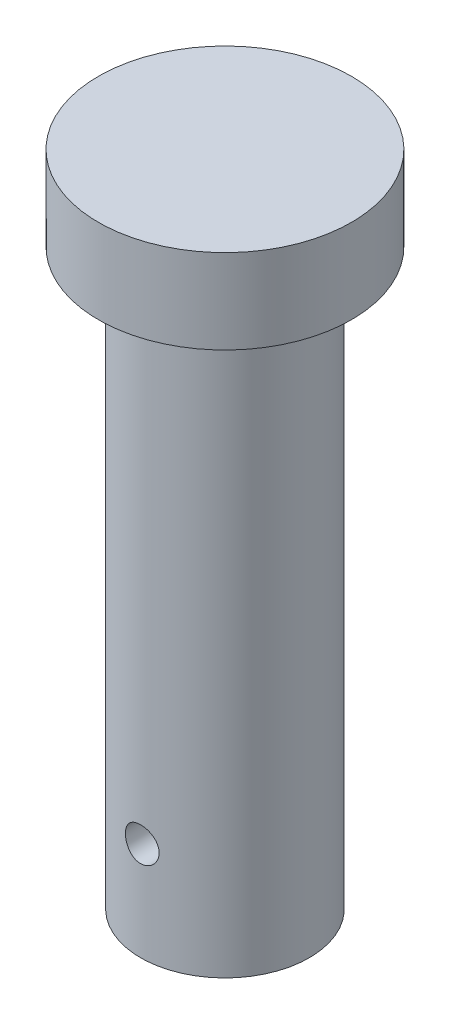
SolidWorks part; units mm, degrees
ref_plane "Front Plane" through (0, 0, 0) normal (0, 0, 1) x (1, 0, 0)
ref_plane "Top Plane" through (0, 0, 0) normal (0, 1, 0) x (1, 0, 0)
ref_plane "Right Plane" through (0, 0, 0) normal (1, 0, 0) x (0, 0, -1)
sketch "Sketch1" plane through (0, 0, 0) normal (0, 0, 1) x (1, 0, 0)
  line L0 (0, 0) -> (0, 117)
  line L1 (0, 117) -> (22.5, 117)
  line L2 (22.5, 117) -> (22.5, 102)
  line L3 (22.5, 102) -> (15, 102)
  line L4 (15, 102) -> (15, 0)
  line L5 (15, 0) -> (0, 0)
  dimension "D1" = 15
  dimension "D2" = 22.5
  dimension "D3" = 15
  dimension "D4" = 102
revolve "Revolve1" add sketch "Sketch1" angle 360 about L0
sketch "Sketch2" plane through (0, 0, 0) normal (0, 0, 1) x (1, 0, 0)
  circle A0 centre (0, 17.5) radius 3
  dimension "D2" = 6
  dimension "D1" = 17.5
extrude "Cut-Extrude1" cut sketch "Sketch2" against normal through all both and the other way through all
